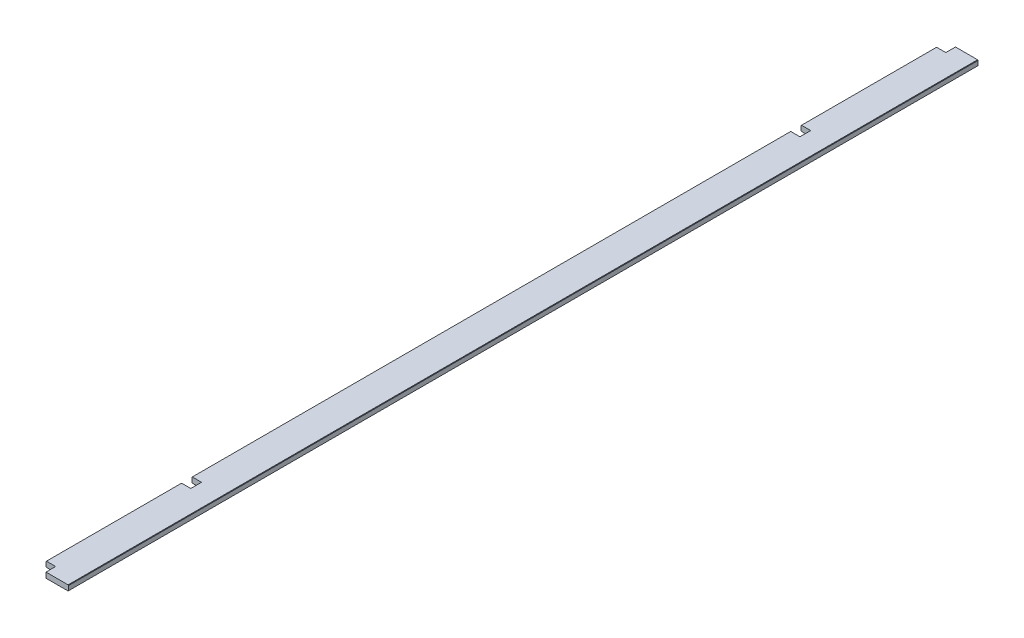
SolidWorks part; units mm, degrees
ref_plane "Спереди" through (0, 0, 0) normal (0, 0, 1) x (1, 0, 0)
ref_plane "Сверху" through (0, 0, 0) normal (0, 1, 0) x (1, 0, 0)
ref_plane "Справа" through (0, 0, 0) normal (1, 0, 0) x (0, 0, -1)
sketch "Эскиз1" plane through (0, 0, 0) normal (0, 0, 1) x (1, 0, 0)
  line L0 (-75, 10.5) -> (-73, 12.5)
  line L1 (-73, 12.5) -> (73, 12.5)
  line L2 (-75, 10.5) -> (-75, -10.5)
  line L3 (-73, -12.5) -> (73, -12.5)
  line L4 (75, 10.5) -> (75, -10.5)
  line L5 (-75, 12.5) -> (75, -12.5) construction
  line L6 (-75, -12.5) -> (75, 12.5) construction
  line L7 (-75, -10.5) -> (-73, -12.5)
  line L8 (73, -12.5) -> (75, -10.5)
  line L9 (73, 12.5) -> (75, 10.5)
  point P0 (0, 0)
  dimension "D1" = 150
  dimension "D2" = 25
extrude "Бобышка-Вытянуть1" add sketch "Эскиз1" along normal blind 4240
sketch "Эскиз2" plane through (0, 12.5, 0) normal (0, 1, 0) x (1, 0, 0)
  line L0 (-75, -4240) -> (-75, 0) construction
  line L1 (-75, 0) -> (-30, 0)
  line L2 (-75, 0) -> (-75, -45)
  line L3 (-75, -45) -> (-30, -45)
  line L4 (-30, 0) -> (-30, -45)
  line L5 (-75, -4240) -> (-30, -4240)
  line L6 (-75, -4240) -> (-75, -4195)
  line L7 (-75, -4195) -> (-30, -4195)
  line L8 (-30, -4240) -> (-30, -4195)
  line L9 (-75, -675) -> (-30, -675)
  line L10 (-75, -675) -> (-75, -725)
  line L11 (-75, -725) -> (-30, -725)
  line L12 (-30, -675) -> (-30, -725)
  line L13 (73, 0) -> (-73, 0) construction
  line L14 (73, -4240) -> (-73, -4240) construction
  line L15 (-75, -3565) -> (-30, -3565)
  line L16 (-75, -3565) -> (-75, -3515)
  line L17 (-75, -3515) -> (-30, -3515)
  line L18 (-30, -3565) -> (-30, -3515)
  dimension "D1" = 45
  dimension "D2" = 45
  dimension "D3" = 45
  dimension "D4" = 45
  dimension "D5" = 45
  dimension "D6" = 50
  dimension "D7" = 725
  dimension "D8" = 50
  dimension "D9" = 45
  dimension "D10" = 725
extrude "Вырез-Вытянуть4" cut sketch "Эскиз2" against normal through all
